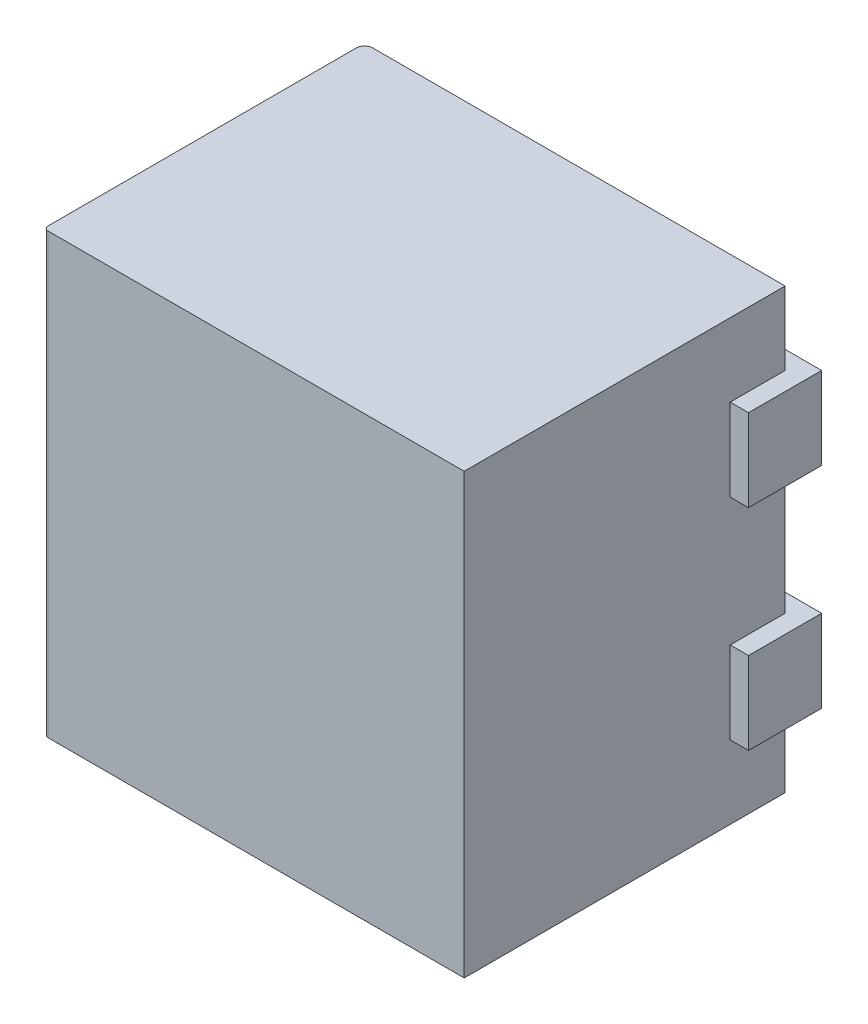
SolidWorks part; units mm, degrees
ref_plane "Front Plane" through (0, 0, 0) normal (0, 0, 1) x (1, 0, 0)
ref_plane "Top Plane" through (0, 0, 0) normal (0, 1, 0) x (1, 0, 0)
ref_plane "Right Plane" through (0, 0, 0) normal (1, 0, 0) x (0, 0, -1)
ref_plane "Plane1" through (0, 0, 0) normal (0, 0, 1) x (1, 0, 0)
sketch "Sketch1" plane through (0, 0, 0) normal (0, 0, 1) x (1, 0, 0)
  line L0 (-2.3, 2.4) -> (2.3, 2.4)
  line L1 (2.3, 2.4) -> (2.3, -2.4)
  line L2 (2.3, -2.4) -> (-2.3, -2.4)
  line L3 (-2.3, -2.4) -> (-2.3, 2.4)
  point P4 (0, 2.4)
  point P5 (2.3, 0)
  dimension "D1" = 4.8
extrude "Boss-Extrude1" add sketch "Sketch1" along normal blind 3.51
fillet "Fillet1" radius 0.09 1 edges at (-2.3, 0, 0)
ref_plane "Plane2" through (0, 0, -0.2) normal (0, 0, 1) x (1, 0, 0)
sketch "Sketch2" plane through (0, 0, -0.2) normal (0, 0, 1) x (1, 0, 0)
  line L0 (-2.5, 0.65) -> (-1.36, 0.65)
  line L1 (-1.36, 0.65) -> (-1.36, -0.65)
  line L2 (-1.36, -0.65) -> (-2.5, -0.65)
  line L3 (-2.5, -0.65) -> (-2.5, 0.65)
  line L4 (1.5, 1.6) -> (2.5, 1.6)
  line L5 (2.5, 1.6) -> (2.5, 0.7)
  line L6 (2.5, 0.7) -> (1.5, 0.7)
  line L7 (1.5, 0.7) -> (1.5, 1.6)
  line L8 (1.5, -0.7) -> (2.5, -0.7)
  line L9 (2.5, -0.7) -> (2.5, -1.6)
  line L10 (2.5, -1.6) -> (1.5, -1.6)
  line L11 (1.5, -1.6) -> (1.5, -0.7)
  point P12 (-1.36, 0)
  point P13 (1.5, 0)
  point P14 (1.5, 1.15)
  point P15 (1.5, -1.15)
  dimension "D1" = 1.14
extrude "Boss-Extrude2" add sketch "Sketch2" along normal blind 0.8
fillet "Fillet2" radius 0.15 1 edges at (-2.5, 0, -0.2)
sketch "Sketch3" plane through (-2.3, 0, 0) normal (-1, 0, 0) x (0, 0, 1)
  line L0 (1.9212, -1.4546) -> (2.8546, -0.5212)
  line L1 (2.3454, -1.8788) -> (3.2788, -0.9454)
  circle A0 centre (2.6, -1.2) radius 0.75
  arc A1 (2.3454, -1.8788) -> (3.2788, -0.9454) centre (2.6, -1.2) ccw
  arc A2 (2.8546, -0.5212) -> (1.9212, -1.4546) centre (2.6, -1.2) ccw
extrude "Cut-Extrude1" cut sketch "Sketch3" against normal blind 0.5
fillet "Fillet3" radius 0.05 1 edges at (-2.3, 0, 3.51)
sketch "Sketch4" plane through (-2.3, 0, 0) normal (-1, 0, 0) x (0, 0, 1)
  circle A0 centre (2.6, -1.2) radius 0.725
extrude "Cut-Extrude2" cut sketch "Sketch4" against normal blind 0.01
